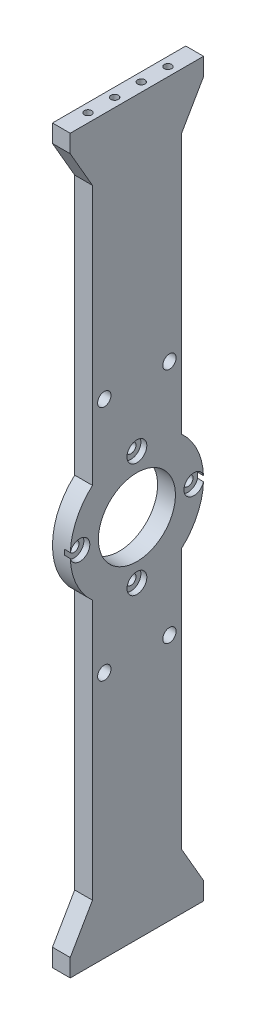
SolidWorks part; units mm, degrees
material "Сплав 2024"
ref_plane "Спереди" through (0, 0, 0) normal (0, 0, 1) x (1, 0, 0)
ref_plane "Сверху" through (0, 0, 0) normal (0, 1, 0) x (1, 0, 0)
ref_plane "Справа" through (0, 0, 0) normal (1, 0, 0) x (0, 0, -1)
sketch "Эскиз1" plane through (0, 0, 0) normal (0, 1, 0) x (1, 0, 0)
  line L1 (0, 0) -> (6, 0)
  line L2 (0, 0) -> (0, -30)
  line L3 (0, -30) -> (6, -30)
  line L4 (6, 0) -> (6, -30)
  dimension "D1" = 6
  dimension "D2" = 30
extrude "Бобышка-Вытянуть1" add sketch "Эскиз1" along normal blind 247
sketch "Эскиз2" plane through (0, 0, 0) normal (-1, 0, 0) x (0, 0, 1)
  line L0 (30, 123.5) -> (0, 123.5) construction
  line L1 (30, 247) -> (30, 0) construction
  line L2 (0, 247) -> (0, 0) construction
  line L3 (15, 247) -> (15, 0) construction
  line L4 (0, 247) -> (30, 247) construction
  line L5 (0, 0) -> (30, 0) construction
  circle A0 centre (15, 123.5) radius 22.5
  dimension "D1" = 45
extrude "Бобышка-Вытянуть2" add sketch "Эскиз2" against normal up to surface (6 mm away) up to face at (6, 123.5, 15)
sketch "Эскиз3" plane through (0, 0, 0) normal (-1, 0, 0) x (0, 0, 1)
  circle A0 centre (15, 123.5) radius 13
  dimension "D1" = 26
extrude "Вырез-Вытянуть1" cut sketch "Эскиз3" against normal through all
sketch "Эскиз4" plane through (6, 0, 0) normal (-1, 0, 0) x (0, 0, 1)
  line L0 (15, 146) -> (15, 101) construction
  line L1 (15, 247) -> (15, 0) construction
  line L2 (37.5, 123.5) -> (-7.5, 123.5) construction
  circle A0 centre (15, 123.5) radius 19.25 construction
  circle A1 centre (15, 123.5) radius 22.5 construction
  dimension "D1" = 38.5
hole_wizard "Цековка для  винта с полукруглой головкой M31" positions "Эскиз6" profile "Эскиз5" counterbore size "M3" standard "Ansi Metric" end condition through all
sketch "Эскиз6" plane through (6, -25.0247, 7.2629) normal (-1, 0, 0) x (0, 0, 1)
  line L0 (7.7371, 171.0247) -> (7.7371, 126.0247) construction
  line L1 (30.2371, 148.5247) -> (-14.7629, 148.5247) construction
  circle A0 centre (7.7371, 148.5247) radius 19.25 construction
  point P0 (7.7371, 167.7747)
  point P6 (-11.5129, 148.5247)
  point P10 (7.7371, 129.2747)
  point P12 (26.9871, 148.5247)
sketch "Эскиз5" plane through (6, 142.75, 15) normal (0, 1, 0) x (0, 0, -1)
  line L0 (0, 0) -> (0, 6)
  line L1 (0, 6) -> (1.7, 6)
  line L3 (1.7, 6) -> (1.7, 2)
  line L4 (1.7, 2) -> (3.35, 2)
  line L5 (3.35, 2) -> (3.35, 0)
  line L7 (3.35, 0) -> (0, 0)
  line L11 (0, -6.35) -> (0, 107.95) construction
  dimension "Диаметр сквозного отверстия" = 3.4
  dimension "Глубина сквозного отверстия" = 6
  dimension "Диаметр цековки" = 6.7
  dimension "Глубина цековки" = 2
sketch "Эскиз8" plane through (6, 0, 0) normal (1, 0, 0) x (0, 0, -1)
  line L0 (-15, 247) -> (-15, 0) construction
  line L1 (-30, 247) -> (0, 247) construction
  line L2 (-30, 0) -> (0, 0) construction
  line L3 (19.447, 123.5) -> (-49.447, 123.5) construction
  line L4 (0, 247) -> (0, 140.2705) construction
  line L5 (-26, 163.5) -> (-4, 163.5) construction
  line L6 (-26, 163.5) -> (-26, 83.5) construction
  line L7 (-26, 83.5) -> (-4, 83.5) construction
  line L8 (-4, 163.5) -> (-4, 83.5) construction
  line L9 (-26, 163.5) -> (-4, 83.5) construction
  line L10 (-26, 83.5) -> (-4, 163.5) construction
  point P8 (-15, 123.5)
  point P9 (-15, 123.5)
  dimension "D1" = 4
  dimension "D2" = 80
hole_wizard "Отверстие с зазором M41" positions "Эскиз10" profile "Эскиз9" hole size "M4" standard "Ansi Metric" end condition through all
sketch "Эскиз10" plane through (6, 0, 0) normal (1, 0, 0) x (0, 0, -1)
  point P0 (-26, 163.5)
  point P3 (-4, 163.5)
  point P6 (-4, 83.5)
  point P9 (-26, 83.5)
sketch "Эскиз9" plane through (6, 163.5, 26) normal (0, 1, 0) x (0, 0, -1)
  line L0 (0, 0) -> (0, 6)
  line L1 (0, 6) -> (2.25, 6)
  line L2 (2.25, 6) -> (2.25, 0)
  line L5 (2.25, 0) -> (0, 0)
  line L11 (0, -6.35) -> (0, 107.95) construction
  dimension "Диаметр сквозного отверстия" = 4.5
  dimension "Глубина сквозного отверстия" = 6
sketch "Эскиз11" plane through (6, 0, 0) normal (1, 0, 0) x (0, 0, -1)
  line L0 (-15, 247) -> (-15, 0) construction
  line L1 (-30, 247) -> (0, 247) construction
  line L2 (-30, 0) -> (0, 0) construction
  line L3 (-37.5, 241) -> (-30, 228.0096)
  line L4 (-37.5, 241) -> (7.5, 241) construction
  line L5 (-37.5, 241) -> (-37.5, 247)
  line L6 (-37.5, 247) -> (7.5, 247)
  line L7 (7.5, 241) -> (7.5, 247)
  line L8 (-37.5, 241) -> (7.5, 247) construction
  line L9 (-37.5, 247) -> (7.5, 241) construction
  line L10 (-30, 247) -> (-30, 140.2705) construction
  line L11 (-30, 228.0096) -> (0, 228.0096)
  line L12 (0, 247) -> (0, 140.2705) construction
  line L13 (0, 228.0096) -> (7.5, 241)
  line L14 (-37.5, 244) -> (7.5, 244) construction
  line L15 (-28.5, 247) -> (-28.5, 241) construction
  line L16 (-19.5, 247) -> (-19.5, 241) construction
  line L17 (-10.5, 247) -> (-10.5, 241) construction
  line L18 (-1.5, 247) -> (-1.5, 241) construction
  line L19 (-15, 123.5) -> (-5.455, 123.5) construction
  line L20 (-1.5, 0) -> (-1.5, 6) construction
  line L21 (-10.5, 0) -> (-10.5, 6) construction
  line L22 (-19.5, 0) -> (-19.5, 6) construction
  line L23 (-28.5, 0) -> (-28.5, 6) construction
  line L24 (-37.5, 3) -> (7.5, 3) construction
  line L25 (-37.5, 0) -> (7.5, 6) construction
  line L26 (-37.5, 6) -> (7.5, 0) construction
  line L27 (-37.5, 6) -> (7.5, 6) construction
  line L28 (0, 18.9904) -> (7.5, 6)
  line L29 (-30, 18.9904) -> (0, 18.9904)
  line L30 (7.5, 6) -> (7.5, 0)
  line L31 (-37.5, 0) -> (7.5, 0)
  line L32 (-37.5, 6) -> (-37.5, 0)
  line L33 (-37.5, 6) -> (-30, 18.9904)
  point P6 (-15, 244)
  point P45 (-15, 3)
  dimension "D1" = 6
  dimension "D2" = 45
  dimension "D3" = 120
  dimension "D4" = 9
  dimension "D5" = 9
  dimension "D6" = 9
  dimension "D7" = 9
extrude "Бобышка-Вытянуть3" add sketch "Эскиз11" against normal up to surface (6 mm away) up to face at (0, 163.5, 23.75)
sketch "Эскиз12" plane through (0, 0, 0) normal (0, -1, 0) x (1, 0, 0)
  line L0 (3, 37.5) -> (3, -7.5) construction
  line L1 (0, 37.5) -> (6, 37.5) construction
  line L2 (0, -7.5) -> (6, -7.5) construction
  line L3 (0, 28.5) -> (6, 28.5) construction
  line L4 (0, -7.5) -> (0, 37.5) construction
  line L5 (6, 37.5) -> (6, -7.5) construction
  line L6 (0, 19.5) -> (6, 19.5) construction
  line L7 (0, 10.5) -> (6, 10.5) construction
  line L8 (0, 1.5) -> (6, 1.5) construction
  line L9 (6, 0) -> (6, 30) construction
  line L10 (0, 0) -> (0, 30) construction
  dimension "D1" = 9
  dimension "D2" = 45
  dimension "D3" = 9
  dimension "D4" = 9
  dimension "D5" = 9
hole_wizard "Отверстие обработанное метчиком M3x0.51" positions "Эскиз14" profile "Эскиз13" tap size "M3x0.5" standard "Ansi Metric"
sketch "Эскиз14" plane through (0, 0, 0) normal (0, -1, 0) x (-1, 0, 0)
  line L0 (0, -28.5) -> (-6, -28.5) construction
  line L1 (0, -19.5) -> (-6, -19.5) construction
  line L2 (0, -10.5) -> (-6, -10.5) construction
  line L3 (0, -1.5) -> (-6, -1.5) construction
  point P0 (-3, -28.5)
  point P4 (-3, -19.5)
  point P8 (-3, -10.5)
  point P12 (-3, -1.5)
sketch "Эскиз13" plane through (3, 0, 28.5) normal (1, 0, 0) x (0, 0, -1)
  line L0 (0, 0) -> (0, 9.2511)
  line L1 (0, 9.2511) -> (1.25, 8.5)
  line L2 (1.25, 8.5) -> (1.25, 0)
  line L5 (1.25, 0) -> (0, 0)
  line L10 (0, 9.2511) -> (-1.25, 8.5) construction
  line L11 (0, -6.35) -> (0, 107.95) construction
  dimension "Диаметр сверла" = 2.5
  dimension "Глубина сверла" = 8.5
  dimension "Угол заточки сверла" = 118
cosmetic thread "Отверстие резьбы1" parameters "D1"=6, "D2"=3
cosmetic thread "Отверстие резьбы2" parameters "D1"=6, "D2"=3
cosmetic thread "Отверстие резьбы3" parameters "D1"=6, "D2"=3
cosmetic thread "Отверстие резьбы4" parameters "D1"=6, "D2"=3
hole_wizard "Отверстие обработанное метчиком M3x0.52" positions "Эскиз16" profile "Эскиз15" tap size "M3x0.5" standard "Ansi Metric"
sketch "Эскиз16" plane through (0, 247, 0) normal (0, 1, 0) x (1, 0, 0)
  line L0 (0, -1.5) -> (6, -1.5) construction
  line L1 (0, -10.5) -> (6, -10.5) construction
  line L2 (0, -19.5) -> (6, -19.5) construction
  line L3 (0, -28.5) -> (6, -28.5) construction
  point P0 (3, -1.5)
  point P4 (3, -10.5)
  point P8 (3, -19.5)
  point P12 (3, -28.5)
sketch "Эскиз15" plane through (3, 247, 1.5) normal (1, 0, 0) x (0, 0, 1)
  line L0 (0, 0) -> (0, 9.2511)
  line L1 (0, 9.2511) -> (1.25, 8.5)
  line L2 (1.25, 8.5) -> (1.25, 0)
  line L5 (1.25, 0) -> (0, 0)
  line L10 (0, 9.2511) -> (-1.25, 8.5) construction
  line L11 (0, -6.35) -> (0, 107.95) construction
  dimension "Диаметр сверла" = 2.5
  dimension "Глубина сверла" = 8.5
  dimension "Угол заточки сверла" = 118
cosmetic thread "Отверстие резьбы5" parameters "D1"=6, "D2"=3
cosmetic thread "Отверстие резьбы6" parameters "D1"=6, "D2"=3
cosmetic thread "Отверстие резьбы7" parameters "D1"=6, "D2"=3
cosmetic thread "Отверстие резьбы8" parameters "D1"=6, "D2"=3
equation "\"D4@Эскиз11\"=\"D2@Эскиз11\"/5"
equation "\"D5@Эскиз11\"=\"D4@Эскиз11\""
equation "\"D6@Эскиз11\"=\"D4@Эскиз11\""
equation "\"D7@Эскиз11\"=\"D4@Эскиз11\""
equation "\"D1@Эскиз12\"=\"D2@Эскиз12\"/5"
equation "\"D3@Эскиз12\"=\"D1@Эскиз12\""
equation "\"D4@Эскиз12\"=\"D1@Эскиз12\""
equation "\"D5@Эскиз12\"=\"D1@Эскиз12\""
